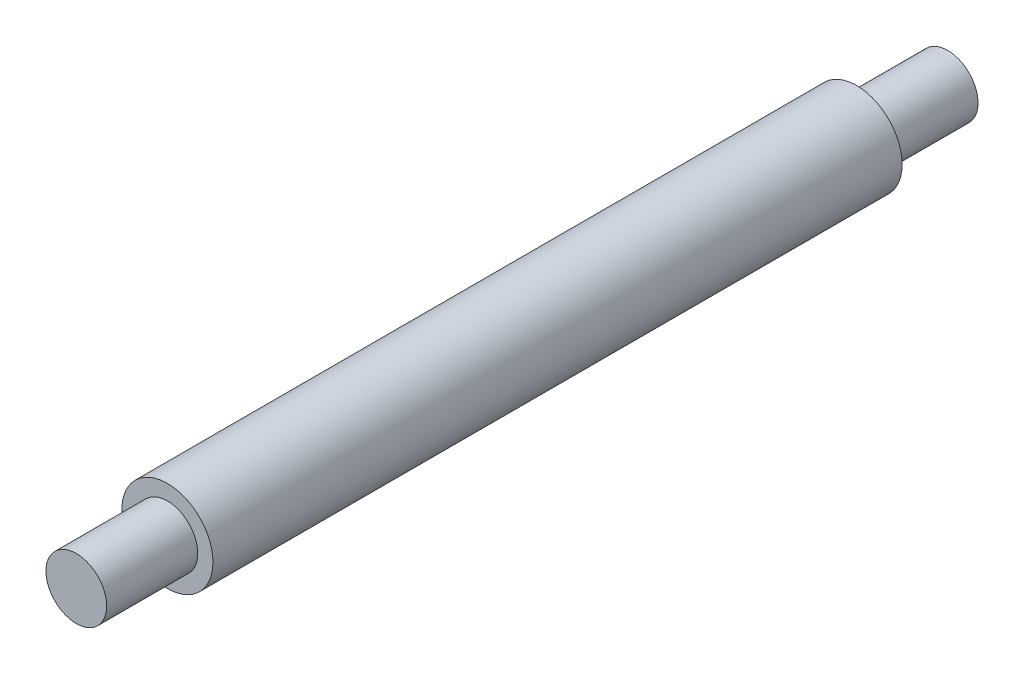
SolidWorks part; units mm, degrees
material "黄铜"
ref_plane "前视基准面" through (0, 0, 0) normal (0, 0, 1) x (1, 0, 0)
ref_plane "上视基准面" through (0, 0, 0) normal (0, 1, 0) x (1, 0, 0)
ref_plane "右视基准面" through (0, 0, 0) normal (1, 0, 0) x (0, 0, -1)
sketch "草图1" plane through (0, 0, 0) normal (0, 0, 1) x (1, 0, 0)
  circle A0 centre (0, 0) radius 1.5
  dimension "D1" = 3
extrude "凸台-拉伸1" add sketch "草图1" along normal blind 22.7
sketch "草图2" plane through (0, 0, 0) normal (0, 0, -1) x (-1, 0, 0)
  circle A0 centre (0, 0) radius 1
  dimension "D1" = 2
extrude "凸台-拉伸2" add sketch "草图2" along normal blind 3
sketch "草图3" plane through (0, 0, 22.7) normal (0, 0, 1) x (1, 0, 0)
  circle A0 centre (0, 0) radius 1
  dimension "D1" = 2
extrude "凸台-拉伸3" add sketch "草图3" along normal blind 3
